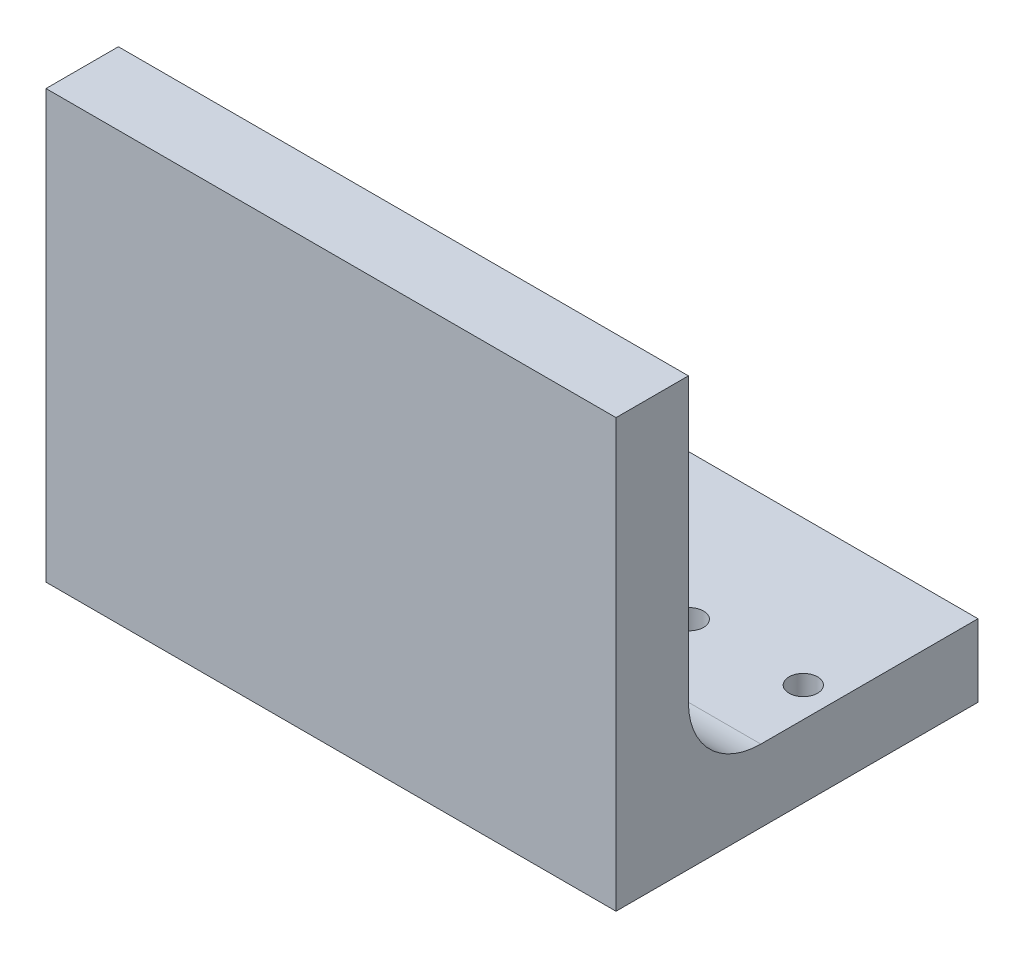
SolidWorks part; units mm, degrees
ref_plane "Front Plane" through (0, 0, 0) normal (0, 0, 1) x (1, 0, 0)
ref_plane "Top Plane" through (0, 0, 0) normal (0, 1, 0) x (1, 0, 0)
ref_plane "Right Plane" through (0, 0, 0) normal (1, 0, 0) x (0, 0, -1)
sketch "Sketch1" plane through (0, 0, 0) normal (0, 0, 1) x (1, 0, 0)
  line L1 (-10, 15) -> (10, 15)
  line L2 (-10, 15) -> (-10, 0)
  line L3 (-10, 0) -> (10, 0)
  line L4 (10, 15) -> (10, 0)
  point P4 (0, 0)
  dimension "D1" = 20
  dimension "D2" = 15
extrude "Boss-Extrude1" add sketch "Sketch1" along normal blind 2.54
sketch "Sketch2" plane through (0, 0, 0) normal (0, 0, -1) x (-1, 0, 0)
  line L0 (10, 0) -> (-10, 0) construction
  line L1 (-10, 0) -> (10, 0)
  line L2 (-10, 0) -> (-10, 2.54)
  line L3 (-10, 2.54) -> (10, 2.54)
  line L4 (10, 0) -> (10, 2.54)
  line L5 (10, 15) -> (10, 0) construction
  line L6 (-10, 0) -> (-10, 15) construction
  dimension "D1" = 2.54
extrude "Boss-Extrude2" add sketch "Sketch2" along normal blind 10.16
sketch "Sketch3" plane through (0, 2.54, 0) normal (0, 1, 0) x (1, 0, 0)
  line L0 (-10, 10.16) -> (10, 10.16) construction
  circle A0 centre (0, 5.08) radius 2.4765
  dimension "D1" = 4.953
  dimension "D2" = 5.08
extrude "Cut-Extrude1" cut sketch "Sketch3" against normal up to next
fillet "Fillet1" radius 2.54 1 edges at (0, 2.54, 0)
sketch "Sketch4" plane through (0, 2.54, 0) normal (0, 1, 0) x (1, 0, 0)
  line L8 (-14.5165, 3.5893) -> (-1.9889, 2.1899)
  line L9 (-1.9, 2.0905) -> (-1.9, -0.97)
  line L10 (1.9, -0.97) -> (1.9, 1.542)
  line L11 (1.9872, 1.6412) -> (17.1415, 3.5923)
  line L12 (17.1415, 6.5677) -> (1.9872, 8.5188)
  line L13 (1.9, 8.618) -> (1.9, 11.83)
  line L14 (-1.9, 11.83) -> (-1.9, 8.0695)
  line L15 (-1.9889, 7.9701) -> (-14.5165, 6.5707)
  line L16 (-14.5165, 3.5893) -> (-1.9889, 2.1899)
  line L17 (-1.9, 2.0905) -> (-1.9, -0.97)
  line L18 (1.9, -0.97) -> (1.9, 1.542)
  line L19 (1.9872, 1.6412) -> (17.1415, 3.5923)
  line L20 (17.1415, 6.5677) -> (1.9872, 8.5188)
  line L21 (1.9, 8.618) -> (1.9, 11.83)
  line L22 (-1.9, 11.83) -> (-1.9, 8.0695)
  line L23 (-1.9889, 7.9701) -> (-14.5165, 6.5707)
  circle A0 centre (-4.35, 5.08) radius 0.5 construction
  circle A1 centre (-8.35, 5.08) radius 0.5 construction
  circle A2 centre (8.95, 5.08) radius 0.5 construction
  circle A3 centre (4.95, 5.08) radius 0.5 construction
  circle A4 centre (-4.35, 5.08) radius 0.5
  circle A5 centre (-8.35, 5.08) radius 0.5
  circle A6 centre (8.95, 5.08) radius 0.5
  circle A7 centre (4.95, 5.08) radius 0.5
  arc A8 (-1.9, 2.0905) -> (-1.9889, 2.1899) centre (-2, 2.0905) ccw
  arc A9 (-1.9, -0.97) -> (1.9, -0.97) centre (0, -0.97) ccw
  arc A10 (1.9872, 1.6412) -> (1.9, 1.542) centre (2, 1.542) ccw
  arc A11 (17.1415, 3.5923) -> (17.1415, 6.5677) centre (16.95, 5.08) ccw
  arc A12 (1.9, 8.618) -> (1.9872, 8.5188) centre (2, 8.618) ccw
  arc A13 (1.9, 11.83) -> (-1.9, 11.83) centre (0, 11.83) ccw
  arc A14 (-1.9889, 7.9701) -> (-1.9, 8.0695) centre (-2, 8.0695) ccw
  arc A15 (-14.5165, 6.5707) -> (-14.5165, 3.5893) centre (-14.35, 5.08) ccw
  arc A16 (-1.9, 2.0905) -> (-1.9889, 2.1899) centre (-2, 2.0905) ccw
  arc A17 (-1.9, -0.97) -> (1.9, -0.97) centre (0, -0.97) ccw
  arc A18 (1.9872, 1.6412) -> (1.9, 1.542) centre (2, 1.542) ccw
  arc A19 (17.1415, 3.5923) -> (17.1415, 6.5677) centre (16.95, 5.08) ccw
  arc A20 (1.9, 8.618) -> (1.9872, 8.5188) centre (2, 8.618) ccw
  arc A21 (1.9, 11.83) -> (-1.9, 11.83) centre (0, 11.83) ccw
  arc A22 (-1.9889, 7.9701) -> (-1.9, 8.0695) centre (-2, 8.0695) ccw
  arc A23 (-14.5165, 6.5707) -> (-14.5165, 3.5893) centre (-14.35, 5.08) ccw
  dimension "D1" = 0
extrude "Cut-Extrude2" cut sketch "Sketch4" against normal blind 10 contours A5 | A4 | A7 | A6
